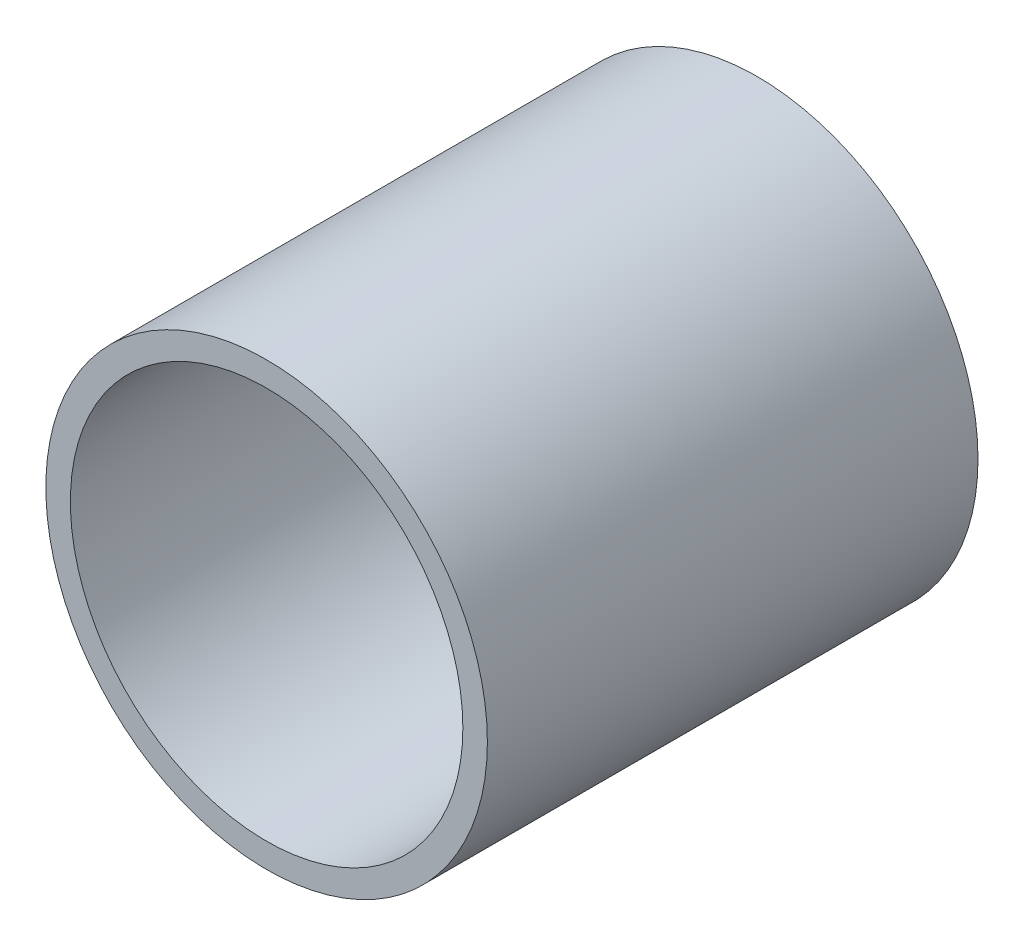
SolidWorks part; units mm, degrees
ref_plane "Front Plane" through (0, 0, 0) normal (0, 0, 1) x (1, 0, 0)
ref_plane "Top Plane" through (0, 0, 0) normal (0, 1, 0) x (1, 0, 0)
ref_plane "Right Plane" through (0, 0, 0) normal (1, 0, 0) x (0, 0, -1)
sketch "Sketch1" plane through (0, 0, 0) normal (0, 0, 1) x (1, 0, 0)
  circle A0 centre (0, 0) radius 50.8
  dimension "D1" = 101.6
extrude "Extrude-Thin1" add sketch "Sketch1" along normal blind 127 thin
